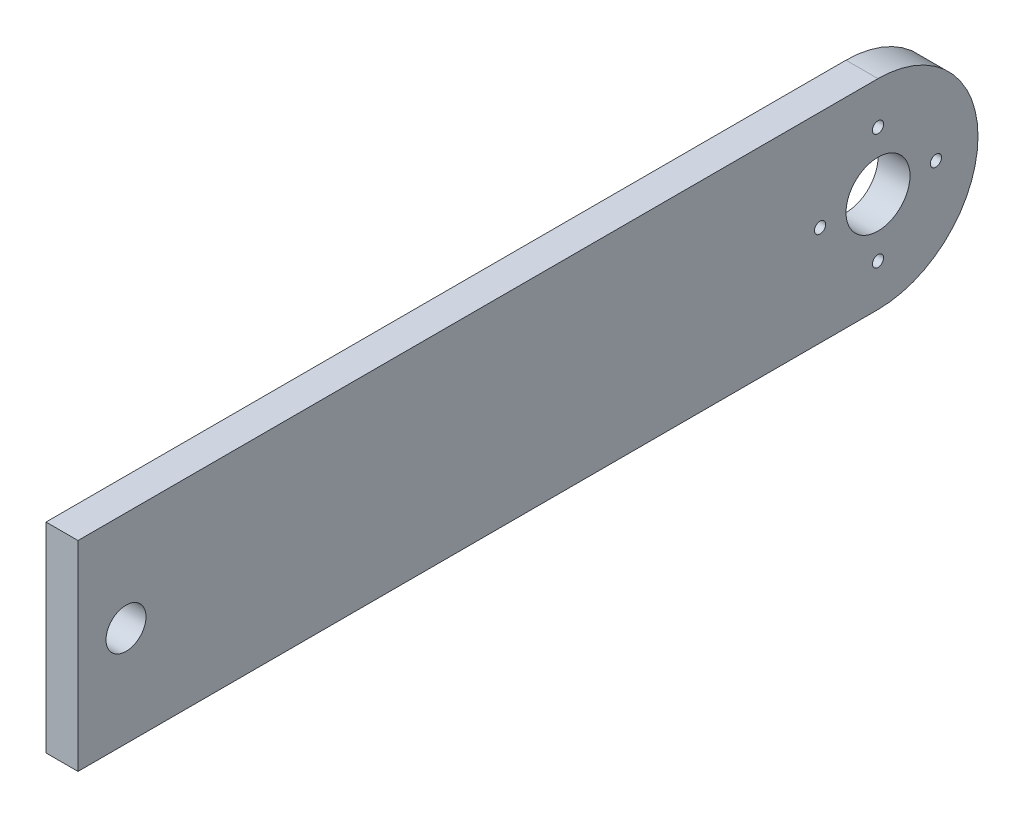
SolidWorks part; units mm, degrees
material "Perspex (TM) GS Acrylic Cast Sheet"
ref_plane "Front Plane" through (0, 0, 0) normal (0, 0, 1) x (1, 0, 0)
ref_plane "Top Plane" through (0, 0, 0) normal (0, 1, 0) x (1, 0, 0)
ref_plane "Right Plane" through (0, 0, 0) normal (1, 0, 0) x (0, 0, -1)
sketch "Sketch1" plane through (0, 0, 0) normal (1, 0, 0) x (0, 0, -1)
  line L0 (-100, 12.5) -> (-100, -12.5)
  line L19 (-100, 12.5) -> (0, 12.5)
  line L20 (-100, -12.5) -> (0, -12.5)
  circle A0 centre (0, 0) radius 4
  circle A1 centre (-7.24, 0) radius 0.7
  circle A2 centre (0, 7.24) radius 0.7
  circle A3 centre (7.24, 0) radius 0.7
  circle A4 centre (0, -7.24) radius 0.7
  arc A5 (0, -12.5) -> (0, 12.5) centre (0, 0) ccw
  point P18 (0, 0)
  dimension "D1" = 8
  dimension "D2" = 1.4
  dimension "D5" = 100
  dimension "D9" = 25
  dimension "D3" = 7.24
  dimension "D4" = 4
extrude "Boss-Extrude1" add sketch "Sketch1" along normal blind 4
sketch "Sketch2" plane through (4, 0, 0) normal (1, 0, 0) x (0, 0, -1)
  line L0 (0, 0) -> (-100, 0) construction
  line L1 (-100, 12.5) -> (-100, -12.5) construction
sketch "Sketch3" plane through (4, 0, 0) normal (1, 0, 0) x (0, 0, -1)
  line L0 (0, 0) -> (-100, 0) construction
  circle A0 centre (-94, 0) radius 2.5
  dimension "D1" = 5
  dimension "D2" = 94
extrude "Cut-Extrude1" cut sketch "Sketch3" against normal blind 10
